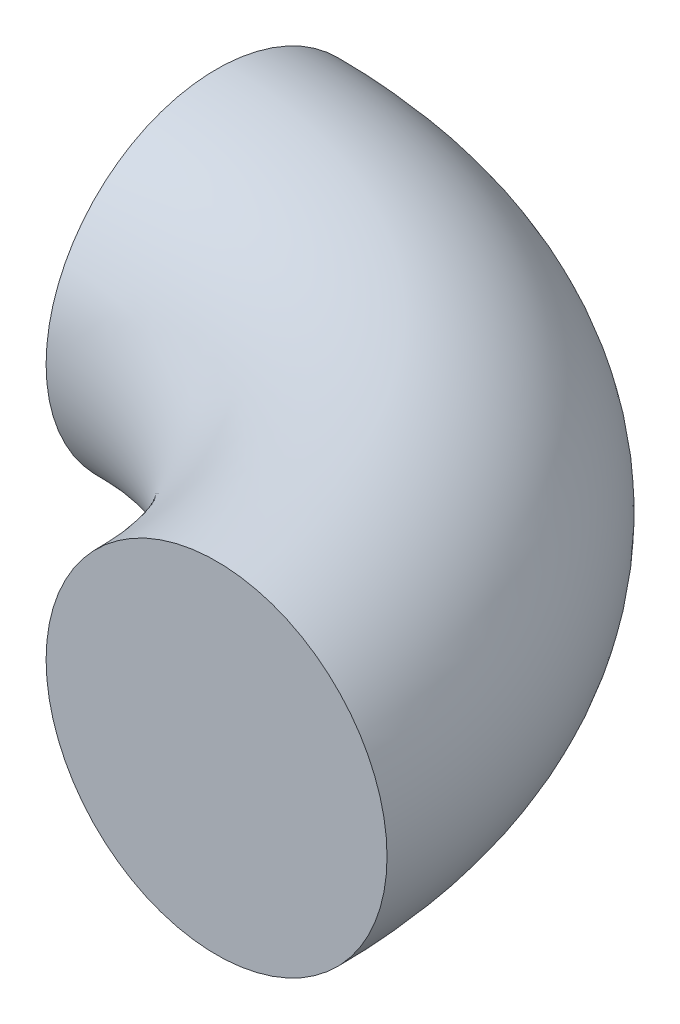
SolidWorks part; units mm, degrees
ref_plane "Front Plane" through (0, 0, 0) normal (0, 0, 1) x (1, 0, 0)
ref_plane "Top Plane" through (0, 0, 0) normal (0, 1, 0) x (1, 0, 0)
ref_plane "Right Plane" through (0, 0, 0) normal (1, 0, 0) x (0, 0, -1)
sketch "Sketch1" plane through (0, 0, 0) normal (0, 0, 1) x (1, 0, 0)
  line L0 (0, -3) -> (0, 3) construction
  circle A0 centre (5, 0) radius 2
revolve "Revolve1" add sketch "Sketch1" angle 90 about L0
